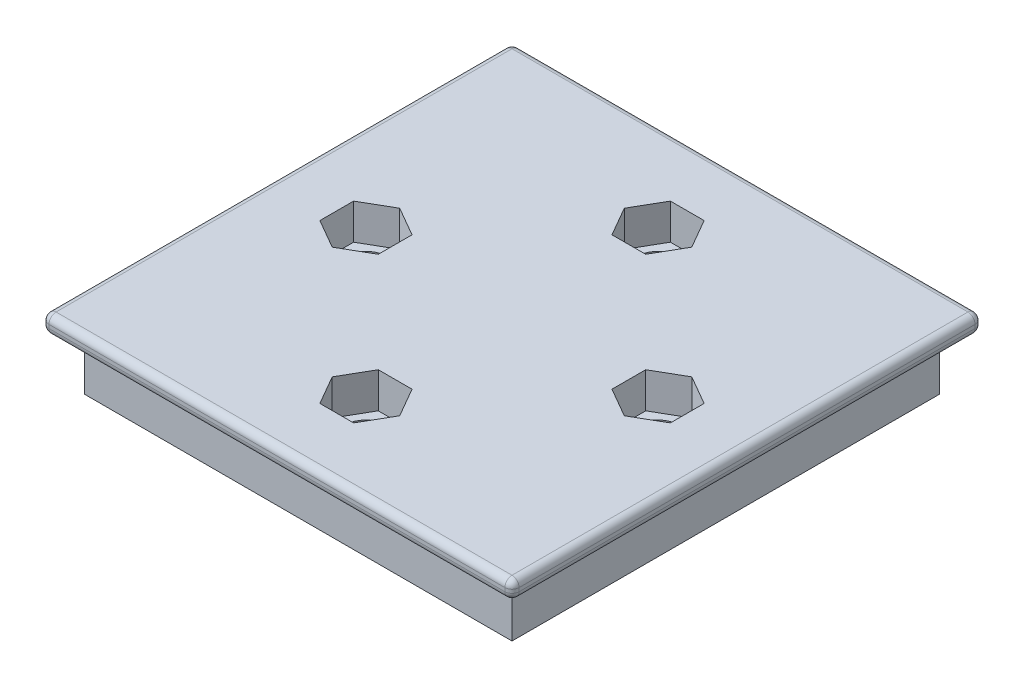
SolidWorks part; units mm, degrees
material "PLA+"
ref_plane "Front Plane" through (0, 0, 0) normal (0, 0, 1) x (1, 0, 0)
ref_plane "Top Plane" through (0, 0, 0) normal (0, 1, 0) x (1, 0, 0)
ref_plane "Right Plane" through (0, 0, 0) normal (1, 0, 0) x (0, 0, -1)
sketch "Sketch1" plane through (0, 0, 0) normal (0, 1, 0) x (1, 0, 0)
  line L1 (30, 30) -> (-30, 30)
  line L2 (30, 30) -> (30, -30)
  line L3 (30, -30) -> (-30, -30)
  line L4 (-30, 30) -> (-30, -30)
  line L5 (30, 30) -> (-30, -30) construction
  line L6 (30, -30) -> (-30, 30) construction
  circle A0 centre (0, 20.5) radius 3
  circle A1 centre (20.5, 0) radius 3
  circle A2 centre (0, -20.5) radius 3
  circle A3 centre (-20.5, 0) radius 3
  point P0 (0, 0)
  dimension "D3" = 6
  dimension "D4" = 6
  dimension "D5" = 6
  dimension "D6" = 6
  dimension "D1" = 60
  dimension "D2" = 60
  dimension "D7" = 41
  dimension "D8" = 41
  dimension "D9" = 20.5
  dimension "D10" = 20.5
extrude "Boss-Extrude1" add sketch "Sketch1" along normal blind 10
sketch "Sketch2" plane through (0, 10, 0) normal (0, 1, 0) x (1, 0, 0)
  line L11 (30, 30) -> (-30, 30)
  line L12 (30, 30) -> (30, -30)
  line L13 (30, -30) -> (-30, -30)
  line L14 (33, 33) -> (-33, 33)
  line L15 (33, -33) -> (33, 33)
  line L16 (-33, -33) -> (33, -33)
  line L17 (-33, 33) -> (-33, -33)
  line L18 (33, 33) -> (-33, 33)
  line L19 (33, -33) -> (33, 33)
  line L20 (-33, -33) -> (33, -33)
  line L21 (-33, 33) -> (-33, -33)
  line L22 (-30, 30) -> (-30, -30)
  line L23 (30, 30) -> (-30, -30) construction
  line L24 (30, -30) -> (-30, 30) construction
  point P0 (0, 0)
  dimension "D1" = 3
extrude "Boss-Extrude2" add sketch "Sketch2" against normal blind 2.5 contours L18 L21 L20 L19
sketch "Sketch3" plane through (0, 10, 0) normal (0, 1, 0) x (1, 0, 0)
  line L0 (-4.7343, 20.5) -> (-2.3671, 16.4)
  line L1 (-20.5, -4.7343) -> (-16.4, -2.3671)
  line L2 (-16.4, -2.3671) -> (-16.4, 2.3671)
  line L3 (-16.4, 2.3671) -> (-20.5, 4.7343)
  line L4 (-20.5, 4.7343) -> (-24.6, 2.3671)
  line L5 (-24.6, 2.3671) -> (-24.6, -2.3671)
  line L6 (-24.6, -2.3671) -> (-20.5, -4.7343)
  line L7 (-2.3671, 16.4) -> (2.3671, 16.4)
  line L8 (2.3671, 16.4) -> (4.7343, 20.5)
  line L9 (4.7343, 20.5) -> (2.3671, 24.6)
  line L10 (2.3671, 24.6) -> (-2.3671, 24.6)
  line L11 (-2.3671, 24.6) -> (-4.7343, 20.5)
  line L12 (20.5, 4.7343) -> (16.4, 2.3671)
  line L13 (16.4, 2.3671) -> (16.4, -2.3671)
  line L14 (16.4, -2.3671) -> (20.5, -4.7343)
  line L15 (20.5, -4.7343) -> (24.6, -2.3671)
  line L16 (24.6, -2.3671) -> (24.6, 2.3671)
  line L17 (24.6, 2.3671) -> (20.5, 4.7343)
  line L18 (4.7343, -20.5) -> (2.3671, -16.4)
  line L19 (2.3671, -16.4) -> (-2.3671, -16.4)
  line L20 (-2.3671, -16.4) -> (-4.7343, -20.5)
  line L21 (-4.7343, -20.5) -> (-2.3671, -24.6)
  line L22 (-2.3671, -24.6) -> (2.3671, -24.6)
  line L23 (2.3671, -24.6) -> (4.7343, -20.5)
  circle A0 centre (-20.5, 0) radius 4.1 construction
  point P30 (0, 0)
  point P33 (0, -16.4)
  dimension "D1" = 8.2
  dimension "D2" = 4
extrude "Cut-Extrude1" cut sketch "Sketch3" against normal blind 5
fillet "Fillet1" radius 1 12 edges at (0, 7.5, 33) (0, 10, 33) (-33, 8.75, 33) (-33, 7.5, 0) (-33, 10, 0) (-33, 8.75, -33) (0, 7.5, -33) (0, 10, -33) (33, 8.75, -33) (33, 7.5, 0) (33, 8.75, 33) (33, 10, 0)
